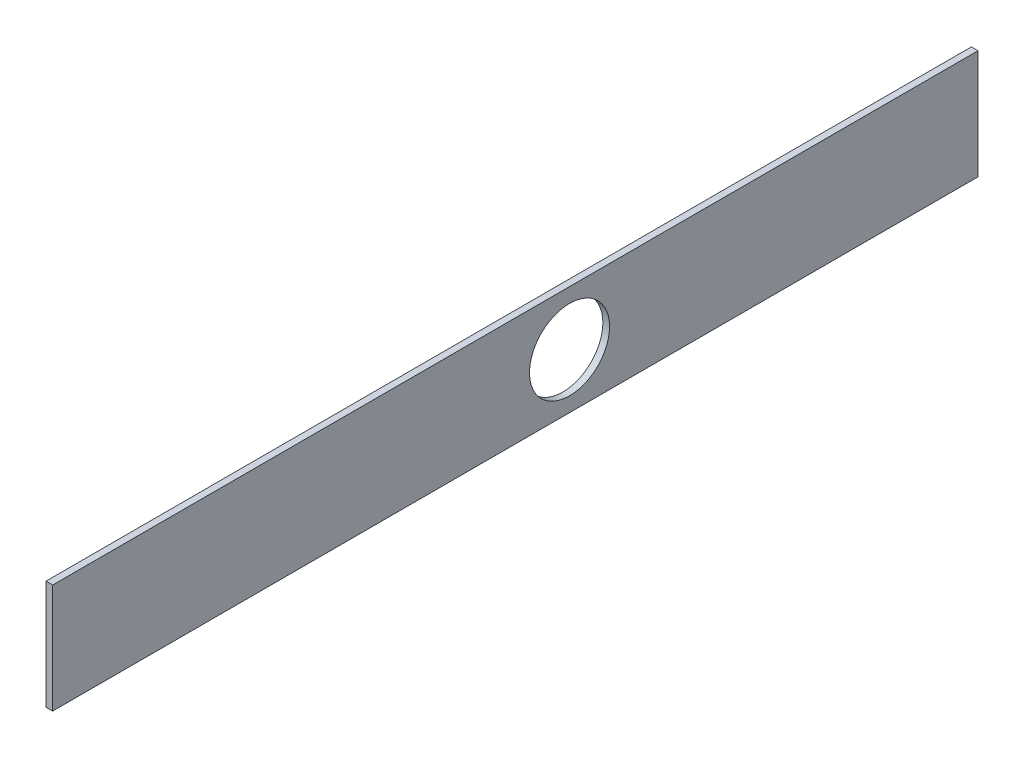
SolidWorks part; units mm, degrees
material "Q355"
ref_plane "前视基准面" through (0, 0, 0) normal (0, 0, 1) x (1, 0, 0)
ref_plane "上视基准面" through (0, 0, 0) normal (0, 1, 0) x (1, 0, 0)
ref_plane "右视基准面" through (0, 0, 0) normal (1, 0, 0) x (0, 0, -1)
sketch "草图1" plane through (0, 0, 0) normal (1, 0, 0) x (0, 0, -1)
  line L1 (-620, 65.5) -> (490, 65.5)
  line L2 (-620, 65.5) -> (-620, -65.5)
  line L3 (-620, -65.5) -> (490, -65.5)
  line L4 (490, 65.5) -> (490, -65.5)
  circle A0 centre (0, 0) radius 48
  dimension "D1" = 620
  dimension "D2" = 1110
  dimension "D4" = 65.5
  dimension "D5" = 96
  dimension "D3" = 131
extrude "凸台-拉伸1" add sketch "草图1" along normal blind 8
